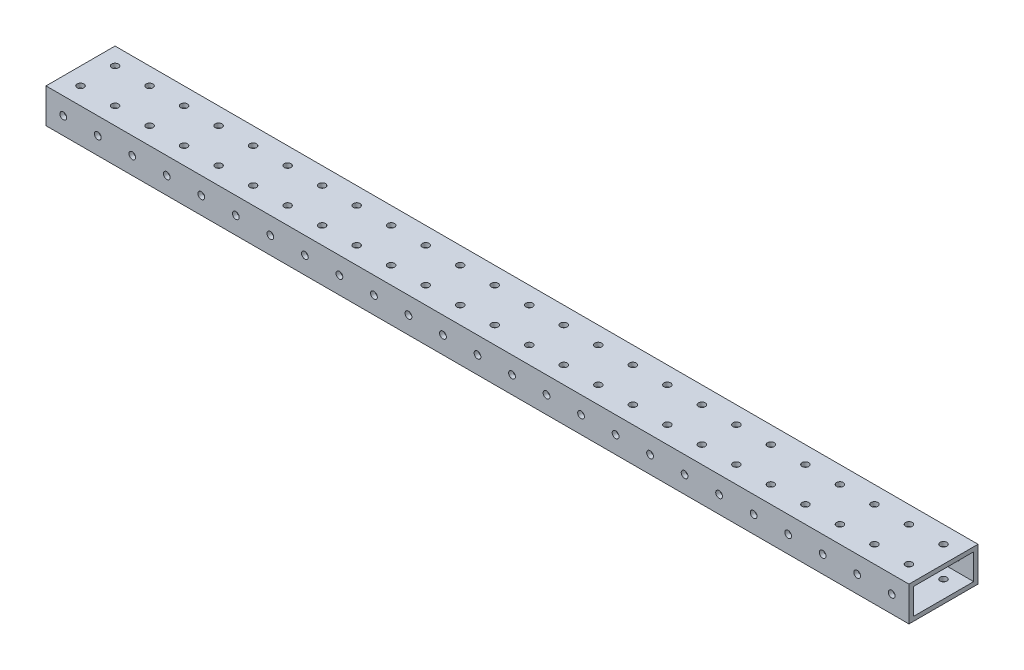
SolidWorks part; units mm, degrees
material "6061-T6 (SS)"
ref_plane "Front Plane" through (0, 0, 0) normal (0, 0, 1) x (1, 0, 0)
ref_plane "Top Plane" through (0, 0, 0) normal (0, 1, 0) x (1, 0, 0)
ref_plane "Right Plane" through (0, 0, 0) normal (1, 0, 0) x (0, 0, -1)
sketch "Sketch1" plane through (0, 0, 0) normal (0, 1, 0) x (1, 0, 0)
  line L1 (0, 0) -> (635, 0)
  line L2 (0, 0) -> (0, 50.8)
  line L3 (0, 50.8) -> (635, 50.8)
  line L4 (635, 0) -> (635, 50.8)
  dimension "D1" = 635
  dimension "D2" = 50.8
extrude "Boss-Extrude1" add sketch "Sketch1" against normal blind 25.4
shell "Shell1" thickness 3.175
sketch "Sketch2" plane through (0, 0, 0) normal (0, 1, 0) x (1, 0, 0)
  line L0 (635, 50.8) -> (0, 50.8) construction
  line L1 (0, 50.8) -> (0, 0) construction
  circle A0 centre (12.7, 38.1) radius 2.4892
  circle A1 centre (38.1, 38.1) radius 2.4892
  circle A2 centre (63.5, 38.1) radius 2.4892
  circle A3 centre (88.9, 38.1) radius 2.4892
  circle A4 centre (114.3, 38.1) radius 2.4892
  circle A5 centre (139.7, 38.1) radius 2.4892
  circle A6 centre (165.1, 38.1) radius 2.4892
  circle A7 centre (190.5, 38.1) radius 2.4892
  circle A8 centre (215.9, 38.1) radius 2.4892
  circle A9 centre (241.3, 38.1) radius 2.4892
  circle A10 centre (266.7, 38.1) radius 2.4892
  circle A11 centre (292.1, 38.1) radius 2.4892
  circle A12 centre (317.5, 38.1) radius 2.4892
  circle A13 centre (342.9, 38.1) radius 2.4892
  circle A14 centre (368.3, 38.1) radius 2.4892
  circle A15 centre (38.1, 12.7) radius 2.4892
  circle A16 centre (63.5, 12.7) radius 2.4892
  circle A17 centre (88.9, 12.7) radius 2.4892
  circle A18 centre (114.3, 12.7) radius 2.4892
  circle A19 centre (139.7, 12.7) radius 2.4892
  circle A20 centre (165.1, 12.7) radius 2.4892
  circle A21 centre (190.5, 12.7) radius 2.4892
  circle A22 centre (215.9, 12.7) radius 2.4892
  circle A23 centre (241.3, 12.7) radius 2.4892
  circle A24 centre (266.7, 12.7) radius 2.4892
  circle A25 centre (292.1, 12.7) radius 2.4892
  circle A26 centre (317.5, 12.7) radius 2.4892
  circle A27 centre (342.9, 12.7) radius 2.4892
  circle A28 centre (368.3, 12.7) radius 2.4892
  circle A29 centre (12.7, 12.7) radius 2.4892
  circle A30 centre (393.7, 38.1) radius 2.4892
  circle A31 centre (419.1, 38.1) radius 2.4892
  circle A32 centre (444.5, 38.1) radius 2.4892
  circle A33 centre (469.9, 38.1) radius 2.4892
  circle A34 centre (495.3, 38.1) radius 2.4892
  circle A35 centre (520.7, 38.1) radius 2.4892
  circle A36 centre (546.1, 38.1) radius 2.4892
  circle A37 centre (571.5, 38.1) radius 2.4892
  circle A38 centre (596.9, 38.1) radius 2.4892
  circle A39 centre (622.3, 38.1) radius 2.4892
  circle A40 centre (393.7, 12.7) radius 2.4892
  circle A41 centre (419.1, 12.7) radius 2.4892
  circle A42 centre (444.5, 12.7) radius 2.4892
  circle A43 centre (469.9, 12.7) radius 2.4892
  circle A44 centre (495.3, 12.7) radius 2.4892
  circle A45 centre (520.7, 12.7) radius 2.4892
  circle A46 centre (546.1, 12.7) radius 2.4892
  circle A47 centre (571.5, 12.7) radius 2.4892
  circle A48 centre (596.9, 12.7) radius 2.4892
  circle A49 centre (622.3, 12.7) radius 2.4892
  dimension "D1" = 4.9784
  dimension "D4" = 25
  dimension "D2" = 12.7
  dimension "D3" = 12.7
  dimension "D5" = 2
extrude "Cut-Extrude1" cut sketch "Sketch2" against normal through all both and the other way through all
sketch "Sketch3" plane through (0, 0, -50.8) normal (0, 0, -1) x (-1, 0, 0)
  line L0 (-635, -25.4) -> (0, -25.4) construction
  line L1 (0, -25.4) -> (0, 0) construction
  circle A0 centre (-12.7, -12.7) radius 2.4892
  circle A1 centre (-38.1, -12.7) radius 2.4892
  circle A2 centre (-63.5, -12.7) radius 2.4892
  circle A3 centre (-88.9, -12.7) radius 2.4892
  circle A4 centre (-114.3, -12.7) radius 2.4892
  circle A5 centre (-139.7, -12.7) radius 2.4892
  circle A6 centre (-165.1, -12.7) radius 2.4892
  circle A7 centre (-190.5, -12.7) radius 2.4892
  circle A8 centre (-215.9, -12.7) radius 2.4892
  circle A9 centre (-241.3, -12.7) radius 2.4892
  circle A10 centre (-266.7, -12.7) radius 2.4892
  circle A11 centre (-292.1, -12.7) radius 2.4892
  circle A12 centre (-317.5, -12.7) radius 2.4892
  circle A13 centre (-342.9, -12.7) radius 2.4892
  circle A14 centre (-368.3, -12.7) radius 2.4892
  circle A15 centre (-393.7, -12.7) radius 2.4892
  circle A16 centre (-419.1, -12.7) radius 2.4892
  circle A17 centre (-444.5, -12.7) radius 2.4892
  circle A18 centre (-469.9, -12.7) radius 2.4892
  circle A19 centre (-495.3, -12.7) radius 2.4892
  circle A20 centre (-520.7, -12.7) radius 2.4892
  circle A21 centre (-546.1, -12.7) radius 2.4892
  circle A22 centre (-571.5, -12.7) radius 2.4892
  circle A23 centre (-596.9, -12.7) radius 2.4892
  circle A24 centre (-622.3, -12.7) radius 2.4892
  dimension "D1" = 12.7
  dimension "D3" = 4.9784
  dimension "D2" = 12.7
  dimension "D4" = 25
extrude "Cut-Extrude2" cut sketch "Sketch3" against normal through all both and the other way through all
